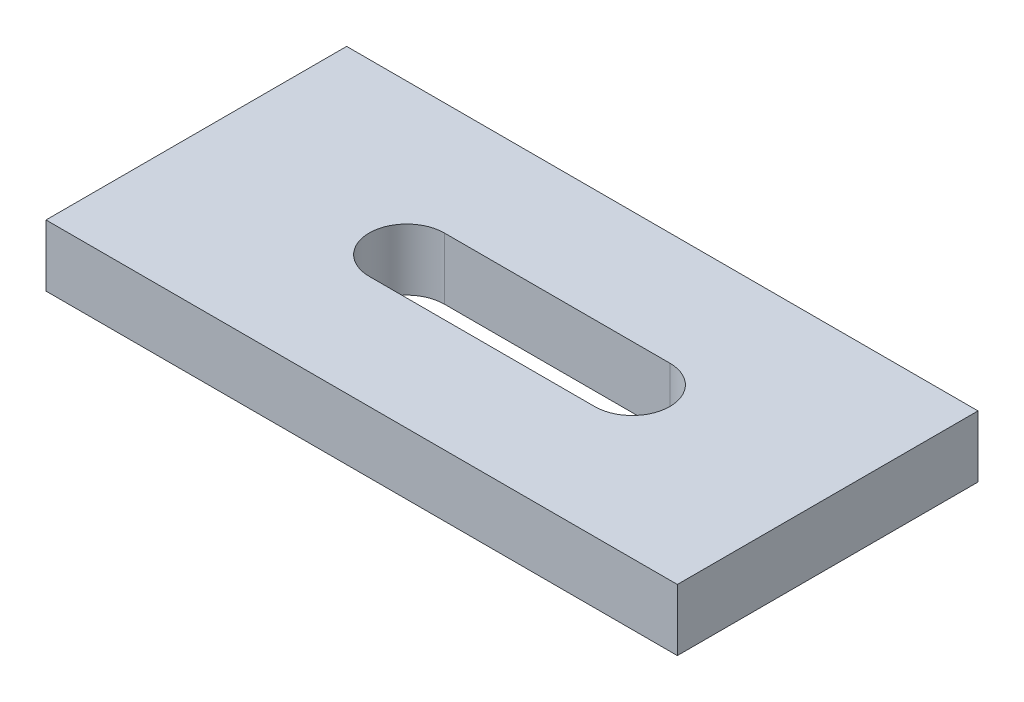
SolidWorks part; units mm, degrees
ref_plane "前视基准面" through (0, 0, 0) normal (0, 0, 1) x (1, 0, 0)
ref_plane "上视基准面" through (0, 0, 0) normal (0, 1, 0) x (1, 0, 0)
ref_plane "右视基准面" through (0, 0, 0) normal (1, 0, 0) x (0, 0, -1)
other "Configuration Table"
sketch "草图1" plane through (0, 0, 0) normal (0, 1, 0) x (1, 0, 0)
  line L1 (0, 0) -> (42, 0)
  line L2 (0, 0) -> (0, 20)
  line L3 (0, 20) -> (42, 20)
  line L4 (42, 0) -> (42, 20)
  dimension "D1" = 42
  dimension "D2" = 20
extrude "凸台-拉伸1" add sketch "草图1" along normal blind 4.1
sketch "草图2" plane through (0, 4.1, 0) normal (0, 1, 0) x (1, 0, 0)
  line L0 (14, 7.5) -> (29, 7.5) construction
  line L1 (29, 12.5) -> (14, 12.5) construction
  line L2 (14, 7.5) -> (29, 7.5)
  line L3 (29, 12.5) -> (14, 12.5)
  arc A0 (29, 7.5) -> (29, 12.5) centre (29, 10) ccw construction
  arc A1 (14, 12.5) -> (14, 7.5) centre (14, 10) ccw construction
  arc A2 (29, 7.5) -> (29, 12.5) centre (29, 10) ccw
  arc A3 (14, 12.5) -> (14, 7.5) centre (14, 10) ccw
extrude "切除-拉伸1" cut sketch "草图2" against normal blind 10
